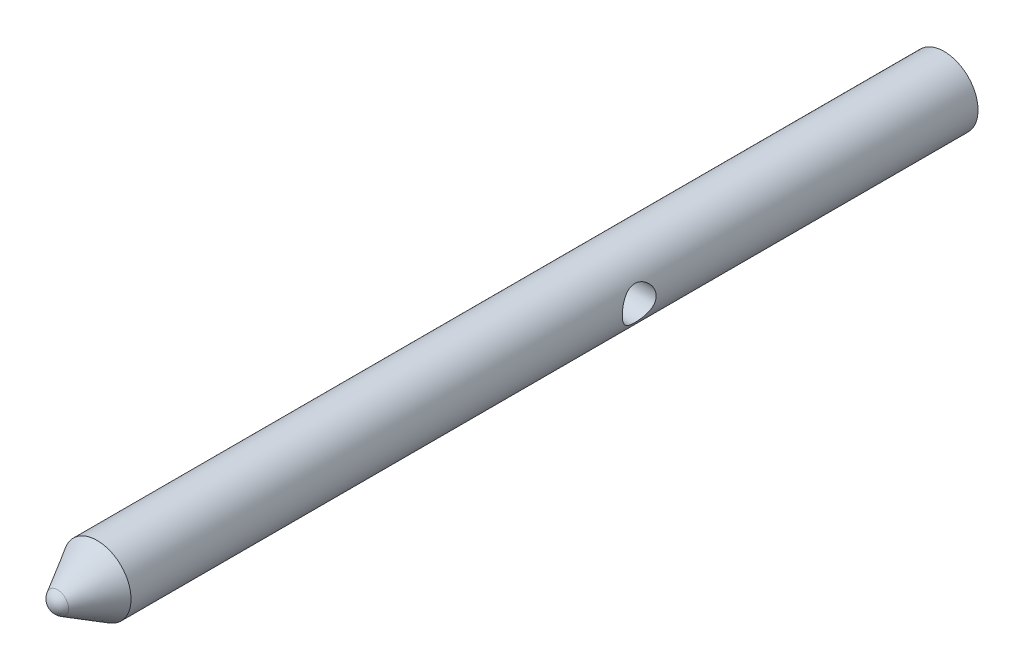
SolidWorks part; units mm, degrees
material "Plain Carbon Steel"
ref_plane "Front Plane" through (0, 0, 0) normal (0, 0, 1) x (1, 0, 0)
ref_plane "Top Plane" through (0, 0, 0) normal (0, 1, 0) x (1, 0, 0)
ref_plane "Right Plane" through (0, 0, 0) normal (1, 0, 0) x (0, 0, -1)
ref_axis "Axis1" through (0, 0, -5) along (0, 0, 1)
sketch "Sketch4" plane through (0, 0, 0) normal (1, 0, 0) x (0, 0, -1)
  line L0 (0, 0) -> (0, 4)
  line L1 (0, 4) -> (-100, 4)
  line L2 (-100, 4) -> (-104.6782, 1.299)
  line L3 (5, 0) -> (-105, 0) construction
  line L4 (-105.4282, 0) -> (0, 0)
  arc A0 (-105.4282, 0) -> (-104.6782, 1.299) centre (-103.9282, 0) cw
  dimension "D4" = 1.5
  dimension "D1" = 30
  dimension "D2" = 4
  dimension "D3" = 100
revolve "Revolve2" add sketch "Sketch4" angle 360 about axis through (0, 0, -5) along (0, 0, 1)
sketch "Sketch5" plane through (0, 0, 0) normal (1, 0, 0) x (0, 0, -1)
  line L0 (5, 0) -> (-105, 0) construction
  line L1 (0, -4) -> (0, 4) construction
  circle A0 centre (-40, 0) radius 2
  dimension "D1" = 4
  dimension "D2" = 40
extrude "Cut-Extrude1" cut sketch "Sketch5" against normal through all both and the other way through all
ref_point "Point1"
